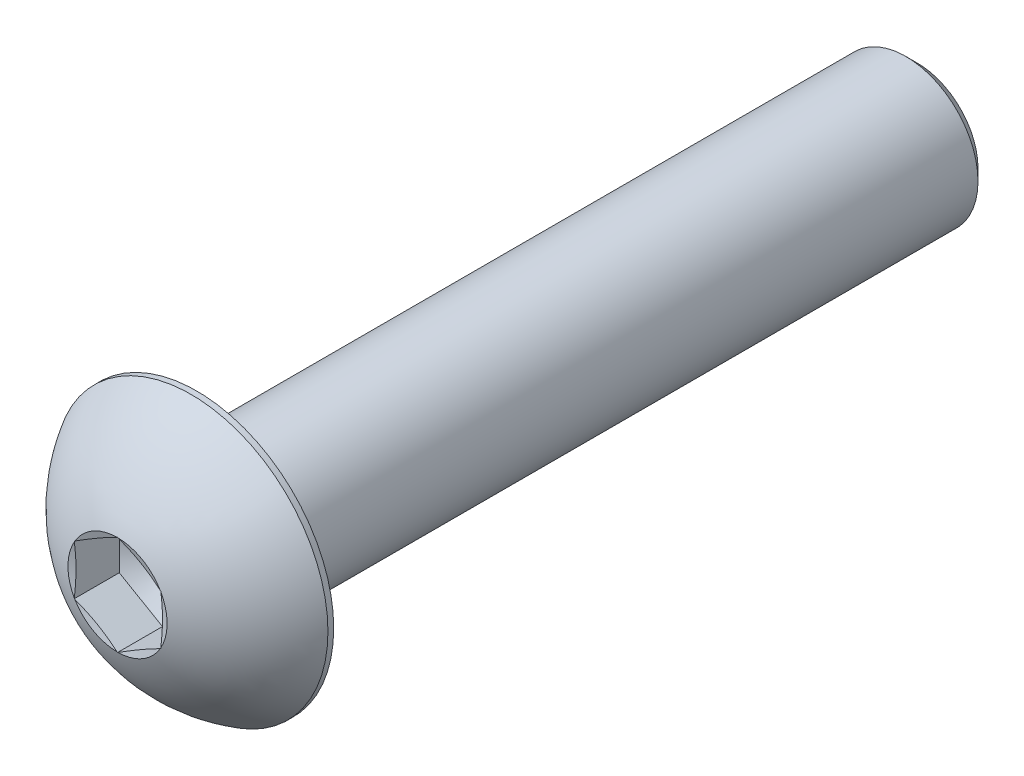
SolidWorks part; units mm, degrees
ref_plane "Front Plane" through (0, 0, 0) normal (0, 0, 1) x (1, 0, 0)
ref_plane "Top Plane" through (0, 0, 0) normal (0, 1, 0) x (1, 0, 0)
ref_plane "Right Plane" through (0, 0, 0) normal (1, 0, 0) x (0, 0, -1)
sketch "Sketch1" plane through (0, 0, 0) normal (1, 0, 0) x (0, 0, -1)
  line L0 (0, 0) -> (31.0773, 0) construction
  line L1 (0, 0) -> (0, 1.72)
  line L3 (27.35, 2.5) -> (2.95, 2.5)
  line L4 (2.75, 2.7) -> (2.75, 4.75)
  line L7 (27.75, 0) -> (0, 0)
  line L8 (27.35, 2.5) -> (27.75, 2.1)
  line L9 (27.75, 2.1) -> (27.75, 0)
  line L10 (2.75, 4.75) -> (2.55, 4.75)
  arc A0 (2.95, 2.5) -> (2.75, 2.7) centre (2.95, 2.7) cw
  arc A6 (2.55, 4.75) -> (0, 1.72) centre (5.4053, -0.241) ccw
  dimension "Rs" = 0.2
  dimension "Rf" = 5.75
  dimension "D3" = 0.2
  dimension "Hole1" = 5
  dimension "Hole2" = 4.2
  dimension "D12" = 45
  dimension "Length" = 25
  dimension "K" = 2.75
  dimension "DL" = 3.44
  dimension "Dk" = 9.5
revolve "Revolve1" add sketch "Sketch1" angle 360 about L0
cosmetic thread "Cosmetic Thread1" parameters "D1"=23.4, "D2"=5
sketch "Sketch2" plane through (0, 0, 0) normal (0, 0, 1) x (1, 0, 0)
  line L0 (0, 0) -> (0, 1.7321) construction
  line L7 (0, -1.7321) -> (1.5, -0.866)
  line L14 (1.5, -0.866) -> (1.5, 0.866)
  line L15 (1.5, 0.866) -> (0, 1.7321)
  line L16 (0, 1.7321) -> (-1.5, 0.866)
  line L17 (-1.5, 0.866) -> (-1.5, -0.866)
  line L18 (-1.5, -0.866) -> (0, -1.7321)
  circle A1 centre (0, 0) radius 1.5 construction
  dimension "D1" = 3
extrude "Cut-Extrude2" cut sketch "Sketch2" against normal blind 1.56
sketch "Sketch5" plane through (0, 0, 0) normal (1, 0, 0) x (0, 0, -1)
  line L3 (0.0589, -1.5) -> (0, -1.72)
  line L4 (0, 0) -> (27.75, 0) construction
  line L5 (27.75, -2.1) -> (27.75, 2.1) construction
  line L6 (0.0589, -1.5) -> (0, -1.5)
  line L7 (0, -1.5) -> (0, -1.72)
  dimension "D1" = 15
  dimension "D2" = 3
  dimension "D3" = 3.44
revolve "Cut-Revolve3" cut sketch "Sketch5" angle 360 about L4
sketch "Sketch4" plane through (0, 0, 0) normal (1, 0, 0) x (0, 0, -1)
  line L0 (1.56, 0) -> (31.2977, 0) construction
  line L1 (1.56, 0) -> (1.56, -1.7321)
  line L5 (1.56, -1.7321) -> (2.56, 0)
  line L7 (2.56, 0) -> (1.56, 0)
  dimension "D1" = 60
revolve "Cut-Revolve2" cut sketch "Sketch4" angle 360 about L0
